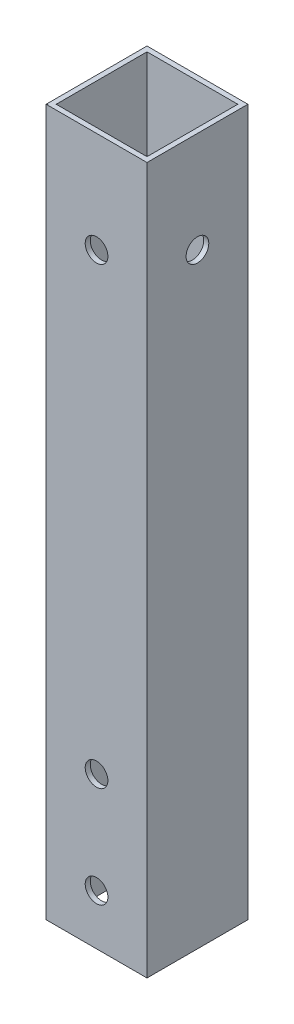
SolidWorks part; units mm, degrees
ref_plane "Front Plane" through (0, 0, 0) normal (0, 0, 1) x (1, 0, 0)
ref_plane "Top Plane" through (0, 0, 0) normal (0, 1, 0) x (1, 0, 0)
ref_plane "Right Plane" through (0, 0, 0) normal (1, 0, 0) x (0, 0, -1)
sketch "Sketch1" plane through (0, 0, 0) normal (0, 1, 0) x (1, 0, 0)
  line L0 (-9, -9) -> (-9, 9)
  line L1 (-10, -10) -> (10, -10)
  line L2 (-10, -10) -> (-10, 10)
  line L3 (-10, 10) -> (10, 10)
  line L4 (10, -10) -> (10, 10)
  line L5 (-10, -10) -> (10, 10) construction
  line L6 (-10, 10) -> (10, -10) construction
  line L7 (-9, 9) -> (9, 9)
  line L8 (9, -9) -> (9, 9)
  line L9 (-9, -9) -> (9, -9)
  point P0 (0, 0)
  dimension "D1" = 20
  dimension "D2" = 20
  dimension "D3" = 1
extrude "Boss-Extrude1" add sketch "Sketch1" along normal blind 140
sketch "Sketch2" plane through (0, 0, 10) normal (0, 0, 1) x (1, 0, 0)
  line L0 (-10, 0) -> (10, 0) construction
  line L1 (-10, 140) -> (10, 140) construction
  circle A0 centre (0, 10) radius 2.25
  circle A1 centre (0, 30) radius 2.25
  circle A2 centre (0, 120) radius 2.25
  dimension "D1" = 4.5
  dimension "D3" = 20
  dimension "D2" = 10
  dimension "D4" = 20
extrude "Cut-Extrude1" cut sketch "Sketch2" against normal through all
sketch "Sketch3" plane through (10, 0, 0) normal (1, 0, 0) x (0, 0, -1)
  line L0 (-10, 140) -> (10, 140) construction
  circle A0 centre (0, 120) radius 2.25
  dimension "D1" = 4.5
  dimension "D2" = 20
extrude "Cut-Extrude2" cut sketch "Sketch3" against normal through all
